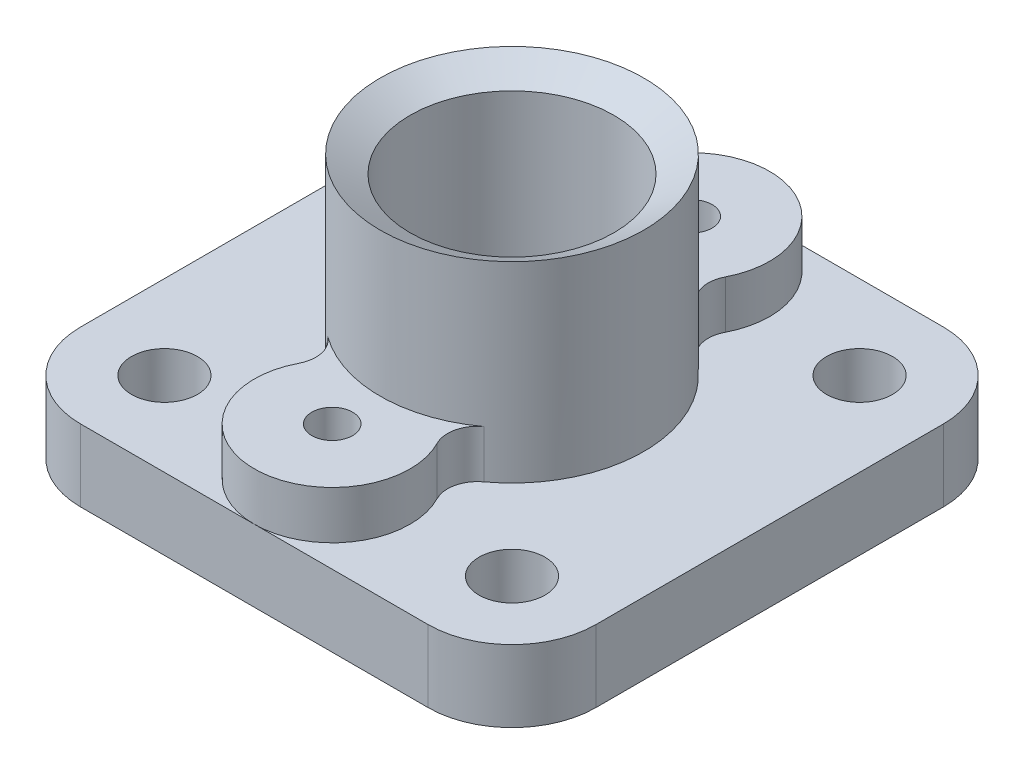
SolidWorks part; units mm, degrees
ref_plane "前视基准面" through (0, 0, 0) normal (0, 0, 1) x (1, 0, 0)
ref_plane "上视基准面" through (0, 0, 0) normal (0, 1, 0) x (1, 0, 0)
ref_plane "右视基准面" through (0, 0, 0) normal (1, 0, 0) x (0, 0, -1)
sketch "草图2" plane through (0, 0, 0) normal (0, 1, 0) x (1, 0, 0)
  line L1 (-29, 43) -> (29, 43)
  line L2 (-43, 29) -> (-43, -29)
  line L3 (-29, -43) -> (29, -43)
  line L4 (43, 29) -> (43, -29)
  line L5 (-43, 43) -> (43, -43) construction
  line L6 (-43, -43) -> (43, 43) construction
  arc A0 (29, 43) -> (43, 29) centre (29, 29) cw
  arc A1 (-43, -29) -> (-29, -43) centre (-29, -29) ccw
  arc A2 (-29, 43) -> (-43, 29) centre (-29, 29) ccw
  arc A3 (29, -43) -> (43, -29) centre (29, -29) ccw
  point P0 (0, 0)
  dimension "D2" = 14
  dimension "D1" = 86
extrude "凸台-拉伸1" add sketch "草图2" along normal blind 12
sketch "草图4" plane through (0, 12, 0) normal (0, 1, 0) x (1, 0, 0)
  line L1 (-29, 29) -> (29, 29) construction
  line L2 (-29, 29) -> (-29, -29) construction
  line L3 (-29, -29) -> (29, -29) construction
  line L4 (29, 29) -> (29, -29) construction
  line L5 (-29, 29) -> (29, -29) construction
  line L6 (-29, -29) -> (29, 29) construction
  circle A0 centre (29, 29) radius 5.5
  circle A1 centre (29, -29) radius 5.5
  circle A2 centre (-29, -29) radius 5.5
  circle A3 centre (-29, 29) radius 5.5
  point P0 (0, 0)
  dimension "D2" = 11
  dimension "D1" = 58
extrude "切除-拉伸1" cut sketch "草图4" against normal through all both and the other way through all
sketch "草图5" plane through (0, 12, 0) normal (0, 1, 0) x (1, 0, 0)
  circle A0 centre (0, 0) radius 22
  dimension "D1" = 44
extrude "凸台-拉伸2" add sketch "草图5" along normal blind 32
sketch "草图6" plane through (0, 12, 0) normal (0, 1, 0) x (1, 0, 0)
  line L0 (0, 0) -> (43, 0) construction
  line L1 (43, -29) -> (43, 29) construction
  circle A0 centre (0, 30) radius 13
  circle A1 centre (0, -30) radius 13
  dimension "D1" = 26
  dimension "D2" = 30
extrude "凸台-拉伸3" add sketch "草图6" along normal blind 8
sketch "草图7" plane through (0, 0, 0) normal (0, -1, 0) x (1, 0, 0)
  circle A0 centre (0, 0) radius 21
  dimension "D1" = 42
extrude "凸台-拉伸4" add sketch "草图7" along normal blind 7
sketch "草图8" plane through (0, -7, 0) normal (0, -1, 0) x (1, 0, 0)
  line L0 (0, 0) -> (21, 0)
  line L1 (0, 0) -> (-18.1865, -10.5)
  circle A0 centre (0, 0) radius 15
  circle A1 centre (0, 0) radius 21 construction
  circle A2 centre (0, 0) radius 21 construction
  circle A4 centre (0, 0) radius 21
  circle A5 centre (0, 0) radius 21
  point P11 (0, 0)
  circle M5 centre (0, 0) radius 21
  dimension "D1" = 30
  dimension "D2" = 30
  dimension "D3" = 0
extrude "凸台-拉伸5" add sketch "草图8" along normal blind 7 contours A0 L1 L0 M5
chamfer "倒角1" distance 1 angle 45 1 edges at (3.8823, -14, -14.4889)
sketch "草图9" plane through (0, 0, 0) normal (0, 0, 1) x (1, 0, 0)
  line L0 (0, 44) -> (0, 0) construction
  line L1 (22, 44) -> (-22, 44) construction
  line L2 (22, 44) -> (17, 41.1132)
  line L3 (17, 41.1132) -> (17, 17)
  line L4 (17, 17) -> (12, 14.1132)
  line L5 (12, 14.1132) -> (12, -7)
  line L6 (-12.9904, -7) -> (15, -7) construction
  line L7 (22, 44) -> (0, 44)
  line L8 (12, -7) -> (0, -7)
  line L9 (0, 44) -> (0, -7)
  dimension "D1" = 27
  dimension "D2" = 34
  dimension "D3" = 120
  dimension "D4" = 24
revolve "切除-旋转1" cut sketch "草图9" angle 360 about L0
hole_wizard "M8 螺纹孔1" positions "3D草图1" profile "草图10" tap size "M8" standard "GB"
sketch3d "3D草图1"
  arc A0 (-8.5987, 20, 20.25) -> (8.5987, 20, 20.25) centre (0, 20, 30) ccw construction
  arc A1 (8.5987, 20, -20.25) -> (-8.5987, 20, -20.25) centre (0, 20, -30) ccw construction
  point P0 (0, 20, -30)
  point P2 (0, 20, 30)
  point P7 (0, 33, 30)
  point P11 (0, 33, -30)
sketch "草图10" plane through (0, 20, -30) normal (1, 0, 0) x (0, 0, 1)
  line L0 (0, 0) -> (0, 20.0429)
  line L1 (0, 20.0429) -> (3.4, 18)
  line L2 (3.4, 18) -> (3.4, 0)
  line L5 (3.4, 0) -> (0, 0)
  line L10 (0, 20.0429) -> (-3.4, 18) construction
  line L11 (0, -6.35) -> (0, 107.95) construction
  dimension "螺纹孔钻头直径" = 6.8
  dimension "螺纹孔钻头深度" = 18
  dimension "导头角度" = 118
cosmetic thread "孔螺蚊线1" parameters "D1"=16, "D2"=8
cosmetic thread "孔螺蚊线2" parameters "D1"=16, "D2"=8
fillet "圆角1" radius 5 4 edges at (8.5987, 16, -20.25) (-8.5987, 16, -20.25) (-8.5987, 16, 20.25) (8.5987, 16, 20.25)
